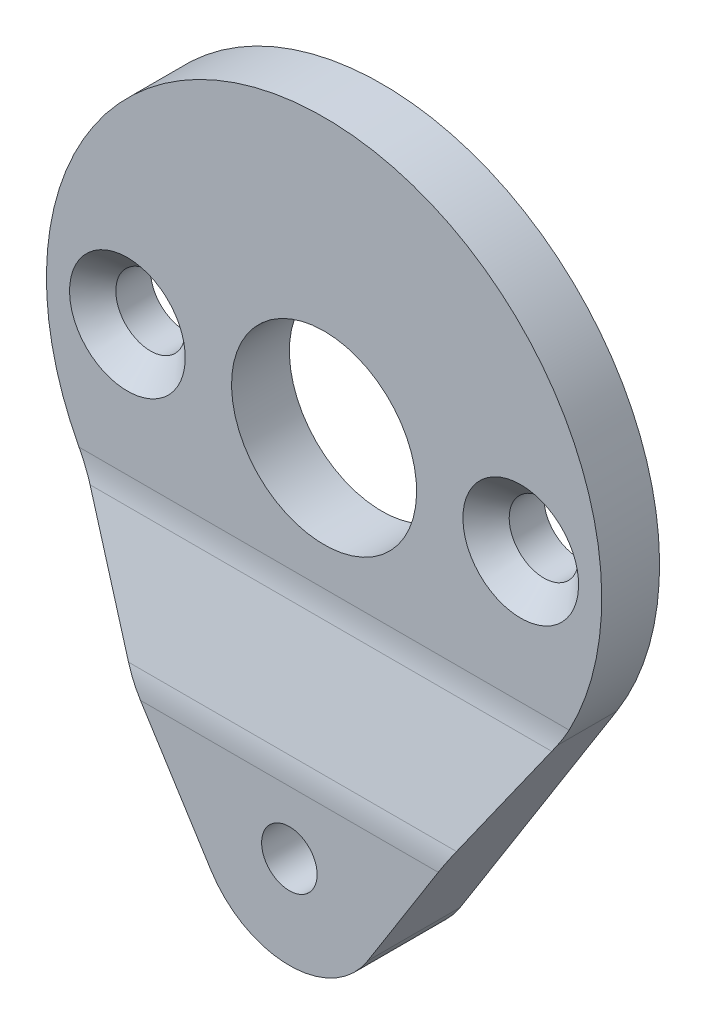
SolidWorks part; units mm, degrees
material "ABS"
ref_plane "Plan de face" through (0, 0, 0) normal (0, 0, 1) x (1, 0, 0)
ref_plane "Plan de dessus" through (0, 0, 0) normal (0, 1, 0) x (1, 0, 0)
ref_plane "Plan de droite" through (0, 0, 0) normal (1, 0, 0) x (0, 0, -1)
sketch "Esquisse1" plane through (0, 0, 0) normal (0, 0, 1) x (1, 0, 0)
  line L0 (-8.5, 0) -> (8.5, 0) construction
  line L1 (-10.1509, -6.4) -> (-3.3836, -17.1333)
  line L2 (10.1509, -6.4) -> (3.3836, -17.1333)
  circle A0 centre (0, 0) radius 4
  arc A1 (10.1509, -6.4) -> (-10.1509, -6.4) centre (0, 0) ccw
  circle A2 centre (0, -15) radius 1.2
  circle A3 centre (-8.5, 0) radius 1.5
  circle A4 centre (8.5, 0) radius 1.5
  arc A5 (-3.3836, -17.1333) -> (3.3836, -17.1333) centre (0, -15) ccw
  dimension "D1" = 24
  dimension "D2" = 8
  dimension "D3" = 3
  dimension "D4" = 2.4
  dimension "D6" = 15
  dimension "D7" = 4
  dimension "D5" = 17
extrude "Boss.-Extru.1" add sketch "Esquisse1" along normal blind 4
sketch "Esquisse2" plane through (0, 0, 0) normal (1, 0, 0) x (0, 0, -1)
  line L0 (-4, -11.7667) -> (-2.5, -6.1686)
  line L1 (-4, -17.1333) -> (-4, -6.4) construction
  line L2 (-2.5, -6.1686) -> (-2.5, 12)
  line L3 (0, 12) -> (-4, 12) construction
  line L4 (-2.5, 12) -> (-4, 12)
  line L5 (-4, 12) -> (-4, -11.7667)
  dimension "D1" = 1.5
  dimension "D2" = 15
extrude "Enlèv. mat.-Extru.1" cut sketch "Esquisse2" against normal mid plane 50
chamfer "Chanfrein1" distance 1 angle 45 2 edges at (8.5, 1.5, 2.5) (-8.5, 1.5, 2.5)
fillet "Congé1" radius 4 2 edges at (0, -6.1686, 2.5) (0, -11.7667, 4)
